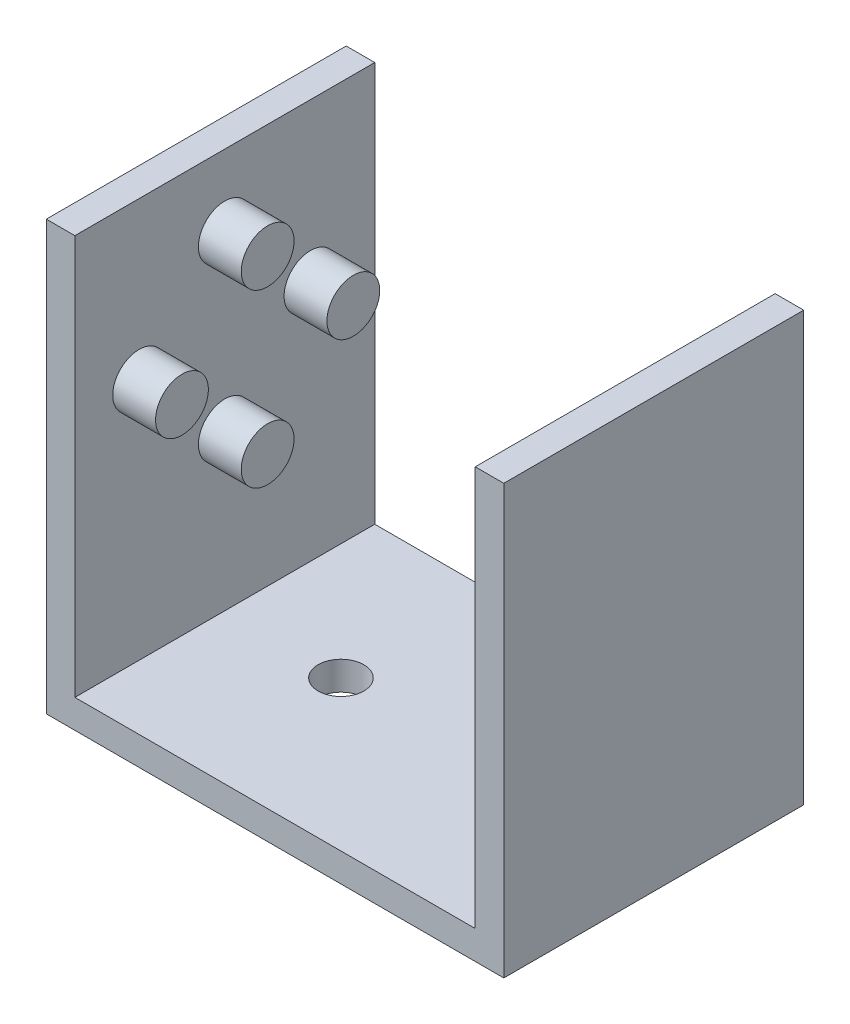
SolidWorks part; units mm, degrees
ref_plane "Front Plane" through (0, 0, 0) normal (0, 0, 1) x (1, 0, 0)
ref_plane "Top Plane" through (0, 0, 0) normal (0, 1, 0) x (1, 0, 0)
ref_plane "Right Plane" through (0, 0, 0) normal (1, 0, 0) x (0, 0, -1)
sketch "Sketch1" plane through (0, 0, 0) normal (0, 0, 1) x (1, 0, 0)
  line L0 (-11.7814, -28.2948) -> (11.6186, -28.2948) construction
  line B0 (12.3207, -8.2948) -> (14.3207, -8.2948)
  line B1 (12.3207, -8.2948) -> (12.3207, -36.2948)
  line B2 (14.3207, -8.2948) -> (14.3207, -38.2948)
  line B3 (14.3207, -38.2948) -> (-17.7147, -38.2948)
  line B4 (12.3207, -36.2948) -> (-15.7147, -36.2948)
  line B5 (-17.7147, -38.2948) -> (-17.7147, -8.2948)
  line B6 (-17.7147, -8.2948) -> (-15.7147, -8.2948)
  line B7 (-15.7147, -36.2948) -> (-15.7147, -8.2948)
sketch_block_instance "Block1-1"
sketch_block "Block1" parameters "D1"=2, "D2"=2, "D3"=2, "D4"=30, "D5"=25.6186
extrude "Boss-Extrude4" add sketch "Sketch1" against normal blind 21
sketch "Sketch2" plane through (-15.7147, 0, 0) normal (1, 0, 0) x (0, 0, -1)
  circle A0 centre (10.5, -25.2948) radius 1.85
  circle A1 centre (16.5, -19.2948) radius 1.85
  circle A2 centre (4.5, -19.2948) radius 1.85
  circle A3 centre (10.5, -13.2948) radius 1.85
extrude "Boss-Extrude5" add sketch "Sketch2" along normal blind 3
sketch "Sketch3" plane through (12.3207, 0, 0) normal (-1, 0, 0) x (0, 0, 1)
  circle A0 centre (-10.5, -19.2948) radius 1.85
  arc A3 (-12.5, -19.2948) -> (-8.5, -19.2948) centre (-10.5, -19.2948) ccw
  arc A4 (-8.5, -19.2948) -> (-12.5, -19.2948) centre (-10.5, -19.2948) ccw
  arc A5 (-12.5, -19.2948) -> (-8.5, -19.2948) centre (-10.5, -19.2948) ccw construction
  arc A6 (-8.5, -19.2948) -> (-12.5, -19.2948) centre (-10.5, -19.2948) ccw construction
  dimension "D1" = 3.7
  dimension "D2" = 0
extrude "Boss-Extrude6" add sketch "Sketch3" along normal blind 3 separate body
sketch "Sketch6" plane through (0, -38.2948, 0) normal (0, -1, 0) x (1, 0, 0)
  line L0 (14.3207, -10.5) -> (-17.7147, -10.5) construction
  line L1 (14.3207, -21) -> (14.3207, 0) construction
  line L2 (-17.7147, -21) -> (-17.7147, 0) construction
  line L3 (-0.0814, 0) -> (-0.0814, -21) construction
  line L4 (11.6186, 0) -> (-11.7814, 0) construction
  circle A0 centre (7.4186, -10.5) radius 1.6
  circle A1 centre (-7.5814, -10.5) radius 1.6
  dimension "D1" = 7.5
extrude "Cut-Extrude1" cut sketch "Sketch6" against normal blind 3
